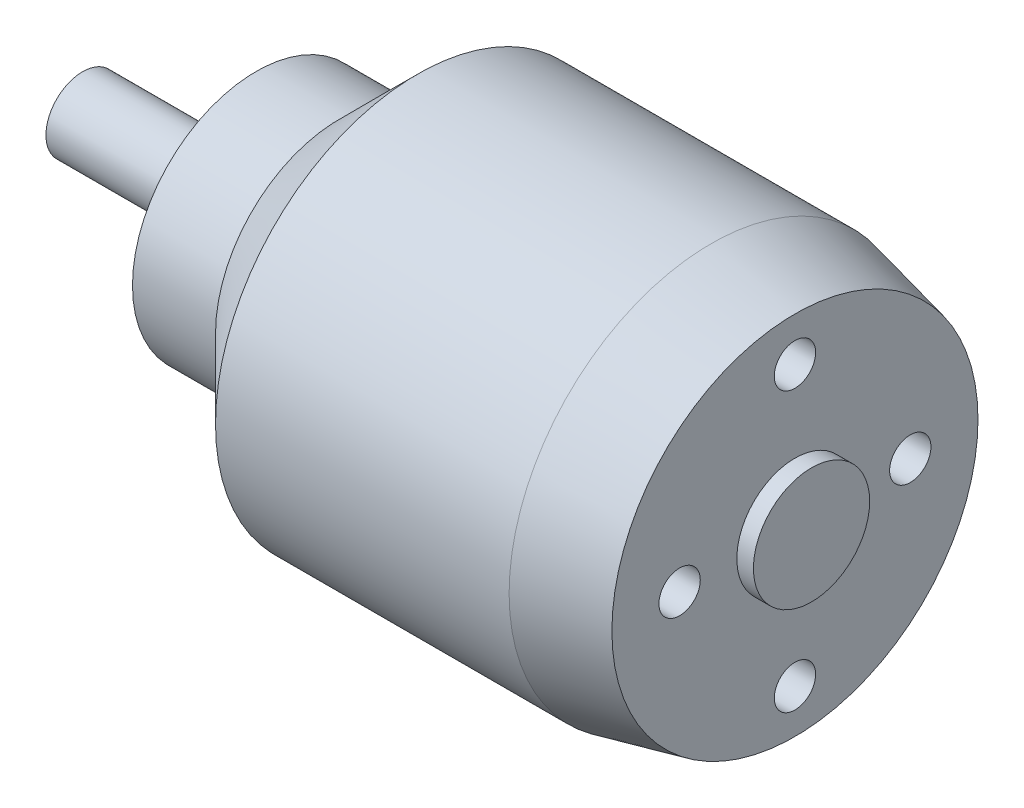
SolidWorks part; units mm, degrees
ref_plane "Front Plane" through (0, 0, 0) normal (1, 0, 0) x (0, 1, 0)
ref_plane "Top Plane" through (0, 0, 0) normal (0, 0, 1) x (0, 1, 0)
ref_plane "Right Plane" through (0, 0, 0) normal (0, 1, 0) x (-1, 0, 0)
sketch "Sketch1" plane through (0, 0, 0) normal (0, 1, 0) x (-1, 0, 0)
  line L0 (0, 0) -> (50.165, 0)
  line L1 (50.165, 0) -> (50.165, 2.5273)
  line L2 (50.165, 2.5273) -> (38.227, 2.5273)
  line L3 (38.227, 2.5273) -> (38.227, 8.509)
  line L4 (38.227, 8.509) -> (32.512, 8.509)
  line L5 (32.512, 8.509) -> (27.1145, 13.9065)
  line L6 (27.1145, 13.9065) -> (6.9088, 13.9065)
  line L7 (6.9088, 13.9065) -> (1.143, 12.5984)
  line L8 (0, 4.0005) -> (0, 0)
  line L9 (0, 4.0005) -> (1.143, 4.0005)
  line L10 (1.143, 4.0005) -> (1.143, 12.5984)
  point P3 (1.143, 12.7068)
  point P10 (2.0199, 13.9065)
  point P14 (4.2281, 13.9065)
  dimension "D1" = 2.5273
  dimension "D2" = 50.165
  dimension "D3" = 1.143
  dimension "D4" = 4.0005
  dimension "D5" = 13.9065
  dimension "D6" = 135
  dimension "D7" = 8.509
  dimension "D8" = 11.938
  dimension "D9" = 5.715
  dimension "D10" = 12.5984
  dimension "D11" = 5.7658
revolve "Revolve1" add sketch "Sketch1" angle 360 about L0
sketch "Sketch2" plane through (-1.143, 0, 0) normal (1, 0, 0) x (0, 1, 0)
  line L0 (0, -7.9375) -> (0, 7.9375) construction
  line L1 (-9.5885, 0) -> (9.5885, 0) construction
  circle A0 centre (0, 7.9375) radius 1.4224
  circle A1 centre (-9.5885, 0) radius 1.4224
  circle A2 centre (0, -7.9375) radius 1.4224
  circle A3 centre (9.5885, 0) radius 1.4224
  point P5 (0, 0)
  point P10 (0, 0)
  dimension "D1" = 2.8448
  dimension "D2" = 19.177
  dimension "D3" = 15.875
extrude "Cut-Extrude1" cut sketch "Sketch2" against normal blind 2.54
